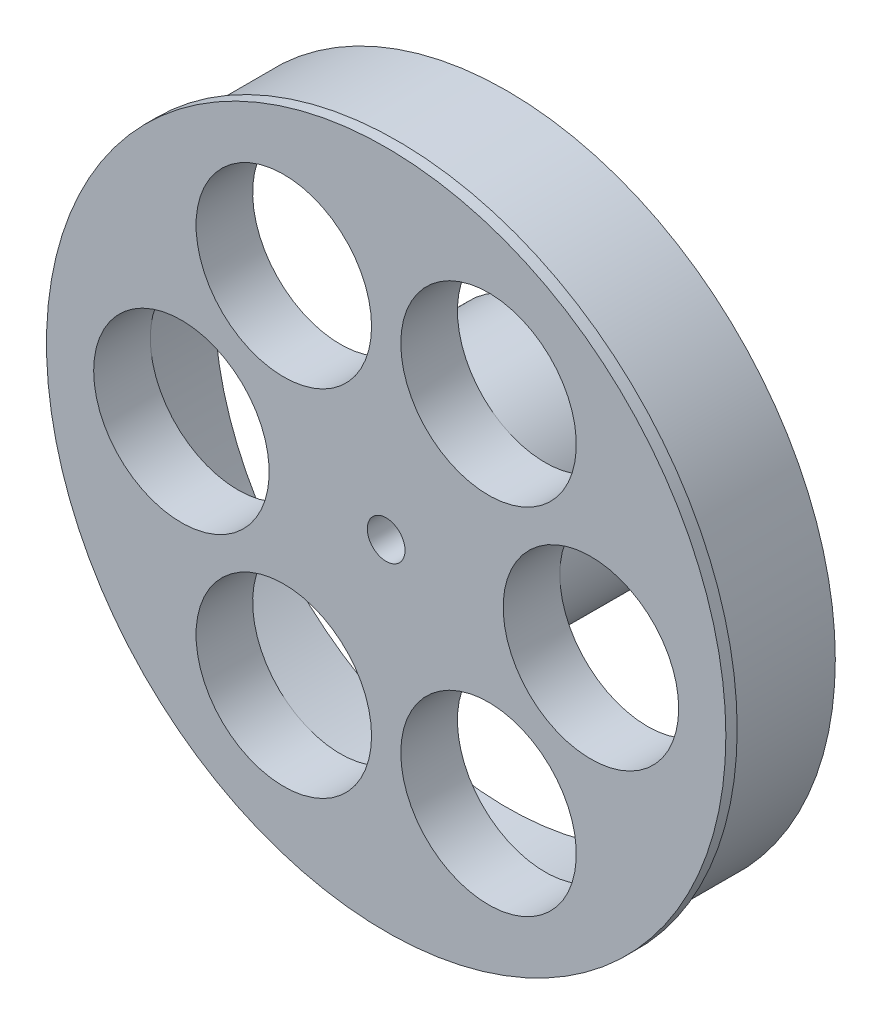
SolidWorks part; units mm, degrees
material "POM Acetal Copolymer"
ref_plane "Front Plane" through (0, 0, 0) normal (0, 0, 1) x (1, 0, 0)
ref_plane "Top Plane" through (0, 0, 0) normal (0, 1, 0) x (1, 0, 0)
ref_plane "Right Plane" through (0, 0, 0) normal (1, 0, 0) x (0, 0, -1)
sketch "Sketch1" plane through (0, 0, 0) normal (1, 0, 0) x (0, 0, -1)
  line L0 (-59.838, 0) -> (69.7594, 0) construction
  line L1 (1.5, 3.1) -> (4.4, 3.1)
  line L2 (0, 9) -> (0.3, 9)
  line L3 (0, 55) -> (0, -55) construction
  line L4 (3.2, 8.7) -> (3.2, 7.75)
  line L5 (3.2, 7.75) -> (1.5, 7.75)
  line L6 (1.5, 7.75) -> (1.5, 3.1)
  line L7 (4.4, 2.1) -> (2.3, 2.1)
  line L8 (0, 0.5) -> (0, 9)
  line L9 (4.4, 3.1) -> (4.4, 2.1)
  line L13 (0.3, 8.7) -> (0.3, 9)
  line L16 (3.2, 8.7) -> (0.3, 8.7)
  line L17 (2.3, 2.1) -> (2.3, 0.5)
  line L18 (2.3, 0.5) -> (0, 0.5)
  point P13 (0, 1.642)
  point P19 (0, 0)
  dimension "D1" = 4.2
  dimension "D2" = 18
  dimension "D3" = 15.5
  dimension "D4" = 1.2
  dimension "D5" = 0.3
  dimension "D6" = 1
  dimension "D7" = 1.5
  dimension "D8" = 0.3
  dimension "D9" = 3.2
  dimension "D10" = 1
  dimension "D11" = 2.1
revolve "Revolve1" add sketch "Sketch1" angle 360 about L0
sketch "Sketch2" plane through (0, 0, 0) normal (0, 0, 1) x (1, 0, 0)
  circle A0 centre (5.425, 0) radius 2.325
  circle A3 centre (0, 0) radius 3.1 construction
  circle A4 centre (0, 0) radius 7.75 construction
extrude "Cut-Extrude1" cut sketch "Sketch2" against normal up to next
pattern_circular "CirPattern1" count 6 over 360 about axis through (0, 0, 0) along (0, 0, 1) of "Cut-Extrude1"
